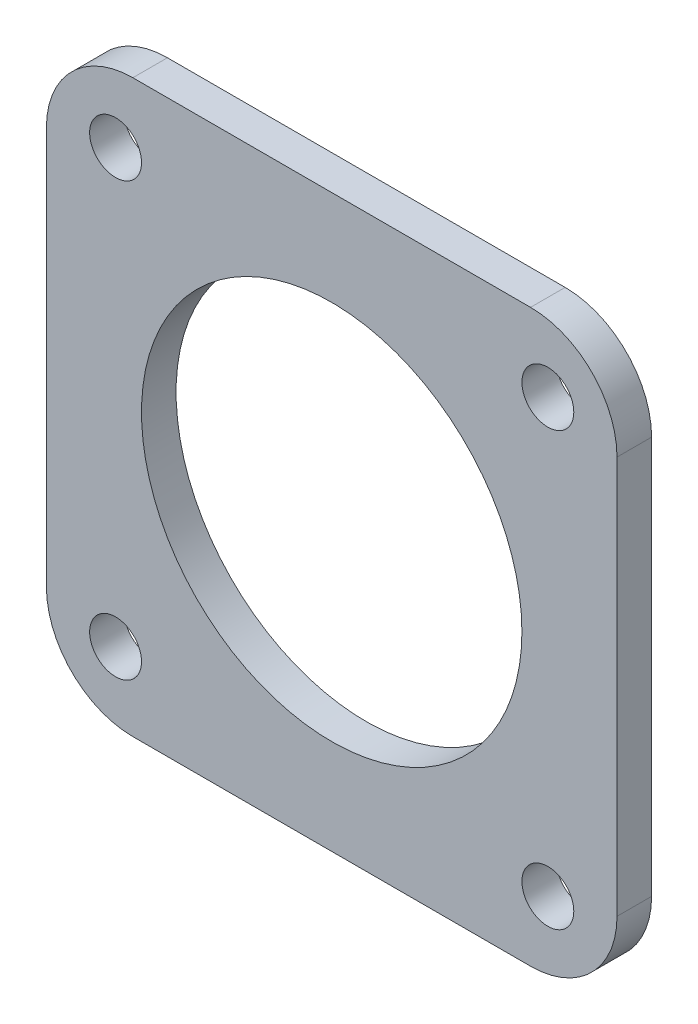
SolidWorks part; units mm, degrees
material "环氧树脂,未充填"
ref_plane "前视基准面" through (0, 0, 0) normal (0, 0, 1) x (1, 0, 0)
ref_plane "上视基准面" through (0, 0, 0) normal (0, 1, 0) x (1, 0, 0)
ref_plane "右视基准面" through (0, 0, 0) normal (1, 0, 0) x (0, 0, -1)
sketch "草图1" plane through (0, 0, 0) normal (0, 0, 1) x (1, 0, 0)
  line L1 (-16.5, 16.5) -> (16.5, 16.5)
  line L2 (-16.5, 16.5) -> (-16.5, -16.5)
  line L3 (-16.5, -16.5) -> (16.5, -16.5)
  line L4 (16.5, 16.5) -> (16.5, -16.5)
  line L5 (-16.5, 16.5) -> (16.5, -16.5) construction
  line L6 (-16.5, -16.5) -> (16.5, 16.5) construction
  point P0 (0, 0)
  dimension "D1" = 33
  dimension "D2" = 33
extrude "凸台-拉伸1" add sketch "草图1" along normal blind 2
sketch "草图2" plane through (0, 0, 2) normal (0, 0, 1) x (1, 0, 0)
  line L1 (-12.5, 12.5) -> (12.5, 12.5) construction
  line L2 (-12.5, 12.5) -> (-12.5, -12.5) construction
  line L3 (-12.5, -12.5) -> (12.5, -12.5) construction
  line L4 (12.5, 12.5) -> (12.5, -12.5) construction
  line L5 (-12.5, 12.5) -> (12.5, -12.5) construction
  line L6 (-12.5, -12.5) -> (12.5, 12.5) construction
  circle A0 centre (-12.5, 12.5) radius 1.5
  circle A1 centre (-12.5, -12.5) radius 1.5
  circle A2 centre (12.5, -12.5) radius 1.5
  circle A3 centre (12.5, 12.5) radius 1.5
  point P0 (0, 0)
  dimension "D2" = 3
  dimension "D1" = 25
extrude "切除-拉伸1" cut sketch "草图2" against normal through all
fillet "圆角1" radius 5 4 edges at (-16.5, 16.5, 1) (-16.5, -16.5, 1) (16.5, -16.5, 1) (16.5, 16.5, 1)
sketch "草图3" plane through (0, 0, 2) normal (0, 0, 1) x (1, 0, 0)
  circle A0 centre (0, 0) radius 11
  dimension "D1" = 22
extrude "切除-拉伸2" cut sketch "草图3" against normal through all
